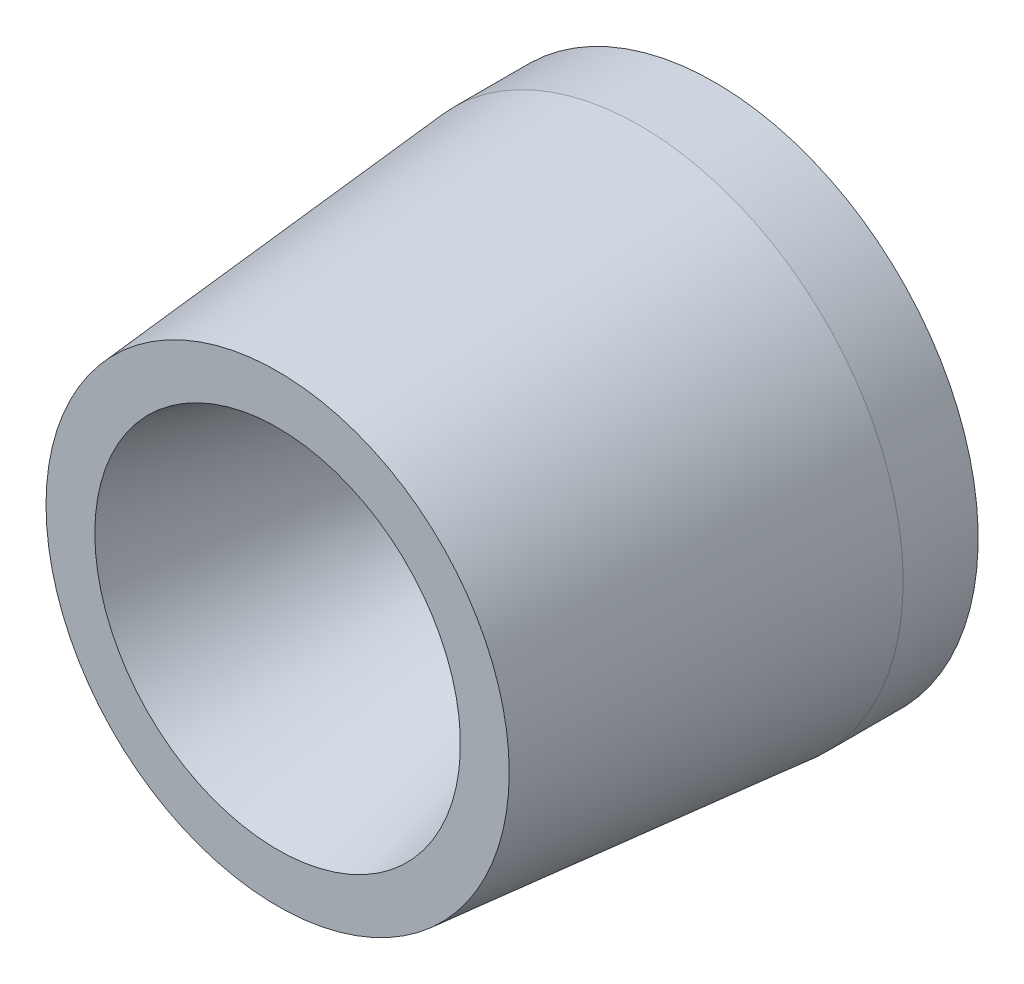
SolidWorks part; units mm, degrees
material "C (Graphite)"
ref_plane "Front Plane" through (0, 0, 0) normal (0, 0, 1) x (1, 0, 0)
ref_plane "Top Plane" through (0, 0, 0) normal (0, 1, 0) x (1, 0, 0)
ref_plane "Right Plane" through (0, 0, 0) normal (1, 0, 0) x (0, 0, -1)
sketch "Sketch1" plane through (0, 0, 0) normal (0, 1, 0) x (1, 0, 0)
  line L8 (59.817, 152.4) -> (18.415, 128.4965) construction
  line L9 (44.323, 130.8334) -> (44.323, 143.5279)
  line L10 (42.8775, 114.3111) -> (44.323, 130.8334)
  line L11 (39.5442, 76.2111) -> (42.8775, 114.3111)
  line L12 (44.323, 130.8334) -> (44.323, 143.4545)
  line L13 (42.8775, 114.3111) -> (44.323, 130.8334)
  line L14 (39.5442, 76.2111) -> (42.8775, 114.3111)
  line L15 (18.415, 128.4965) -> (18.415, 120.8765) construction
  line L16 (18.415, 120.8765) -> (50.8038, 0) construction
  line L17 (44.323, 143.4545) -> (18.415, 128.4965)
  line L18 (18.415, 128.4965) -> (18.415, 120.8765)
  line L19 (18.415, 120.8765) -> (32.0875, 69.85)
  line L20 (39.5442, 76.2111) -> (39.5432, 76.2)
  line L21 (63.246, 76.2) -> (-63.246, 76.2) construction
  line L23 (39.1151, 69.85) -> (-39.1151, 69.85) construction
  line L24 (38.9876, 69.85) -> (32.0875, 69.85)
  line L25 (39.5432, 76.2) -> (38.9876, 69.85)
  line L26 (32.0875, 69.85) -> (-32.0875, 69.85) construction
  dimension "D1" = 0.127
ref_axis "Axis1" through (0, 0, -146.8173) along (0, 0, 1)
revolve "Revolve1" add sketch "Sketch1" angle 360 about axis through (0, 0, -146.8173) along (0, 0, 1)
sketch "Sketch2" plane through (0, 0, 0) normal (0, 1, 0) x (1, 0, 0)
  line L0 (18.415, 120.8765) -> (18.415, 115.9696)
  line L1 (18.415, 120.8765) -> (18.415, 128.4965) construction
  line L2 (32.0875, 69.85) -> (18.415, 120.8765) construction
  line L3 (17.78, 129.5964) -> (43.688, 144.5544)
  line L4 (18.415, 129.963) -> (41.783, 143.4545)
  line L5 (18.415, 128.4965) -> (18.415, 129.963)
  line L6 (18.415, 128.4965) -> (44.323, 143.4545) construction
  line L7 (18.415, 128.4965) -> (44.323, 143.4545)
  line L8 (44.323, 143.4545) -> (41.783, 143.4545)
  line L9 (32.0875, 69.85) -> (18.415, 120.8765)
  line L10 (32.0875, 69.85) -> (30.7727, 69.85)
  line L11 (30.8608, 69.5213) -> (17.1883, 120.5478)
  line L12 (30.7727, 69.85) -> (18.415, 115.9696)
  dimension "D1" = 1.27
  dimension "D2" = 1.27
revolve "Revolve2" add sketch "Sketch2" angle 360 about axis through (0, 0, -146.8173) along (0, 0, 1)
